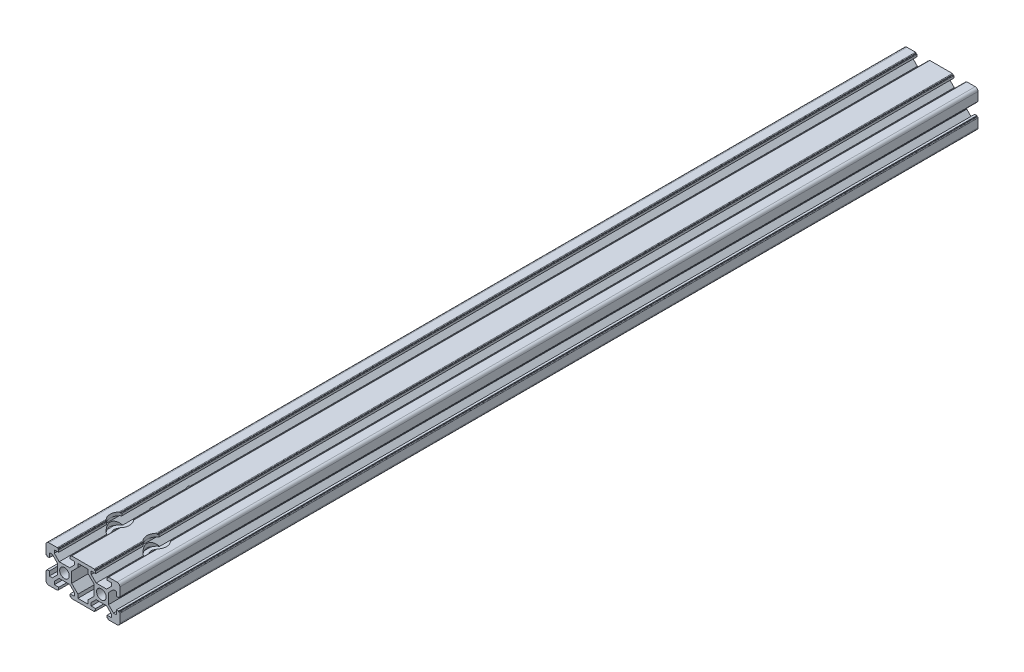
SolidWorks part; units mm, degrees
ref_plane "前视基准面" through (0, 0, 0) normal (0, 0, 1) x (1, 0, 0)
ref_plane "上视基准面" through (0, 0, 0) normal (0, 1, 0) x (1, 0, 0)
ref_plane "右视基准面" through (0, 0, 0) normal (1, 0, 0) x (0, 0, -1)
sketch "草图1" plane through (0, 0, 0) normal (0, 0, 1) x (1, 0, 0)
  line L0 (0, 0) -> (0, -41497.3383) construction
  line L1 (0, 0) -> (41497.3383, 0) construction
  line L2 (-13.9, 0) -> (-13.9, 2.8393)
  line L3 (-13.9, 2.8393) -> (-16.5607, 5.5)
  line L4 (-16.5607, 5.5) -> (-18.2, 5.5)
  line L5 (-18.2, 5.5) -> (-18.2, 3.1)
  line L6 (-18.2, 3.1) -> (-19.4, 3.1)
  line L7 (-19.4, 3.1) -> (-19.4, 3.6)
  line L8 (-19.4, 3.6) -> (-20, 3.6)
  line L9 (-20, 3.6) -> (-20, 10)
  line L10 (-20, 10) -> (-13.6, 10)
  line L11 (-13.6, 10) -> (-13.6, 9.4)
  line L12 (-13.6, 9.4) -> (-13.1, 9.4)
  line L13 (-13.1, 9.4) -> (-13.1, 8.2)
  line L14 (-13.1, 8.2) -> (-15.5, 8.2)
  line L15 (-15.5, 6.5607) -> (-12.8393, 3.9)
  line L16 (-12.8393, 3.9) -> (-7.1607, 3.9)
  line L17 (-4.5, 6.5607) -> (-7.1607, 3.9)
  line L18 (-4.5, 6.5607) -> (-4.5, 8.2)
  line L19 (-4.5, 8.2) -> (-6.9, 8.2)
  line L20 (-6.9, 8.2) -> (-6.9, 9.4)
  line L21 (-6.9, 9.4) -> (-6.4, 9.4)
  line L22 (-6.4, 9.4) -> (-6.4, 10)
  line L23 (-6.4, 10) -> (6.4, 10)
  line L24 (-15.5, 8.2) -> (-15.5, 6.5607)
  line L25 (-10, 0) -> (-20, 10) construction
  line L26 (-6.1, -2.8393) -> (-6.1, 2.8393)
  line L27 (-6.1, 2.8393) -> (-2.7, 6.2393)
  line L28 (-2.7, 6.2393) -> (-2.7, 8.2)
  line L29 (-2.7, 8.2) -> (2.7, 8.2)
  line L30 (-10, 0) -> (0, 10) construction
  line L31 (13.9, 0) -> (13.9, 2.8393)
  line L32 (6.1, -2.8393) -> (6.1, 2.8393)
  line L33 (4.5, 6.5607) -> (7.1607, 3.9)
  line L34 (12.8393, 3.9) -> (7.1607, 3.9)
  line L35 (6.1, 2.8393) -> (2.7, 6.2393)
  line L36 (2.7, 6.2393) -> (2.7, 8.2)
  line L37 (4.5, 6.5607) -> (4.5, 8.2)
  line L38 (6.4, 9.4) -> (6.4, 10)
  line L39 (6.9, 9.4) -> (6.4, 9.4)
  line L40 (6.9, 8.2) -> (6.9, 9.4)
  line L41 (4.5, 8.2) -> (6.9, 8.2)
  line L42 (13.1, 9.4) -> (13.1, 8.2)
  line L43 (13.6, 9.4) -> (13.1, 9.4)
  line L44 (13.6, 10) -> (13.6, 9.4)
  line L45 (20, 10) -> (13.6, 10)
  line L46 (20, 3.6) -> (20, 10)
  line L47 (19.4, 3.6) -> (20, 3.6)
  line L48 (19.4, 3.1) -> (19.4, 3.6)
  line L49 (18.2, 3.1) -> (19.4, 3.1)
  line L50 (18.2, 5.5) -> (18.2, 3.1)
  line L51 (16.5607, 5.5) -> (18.2, 5.5)
  line L52 (13.9, 2.8393) -> (16.5607, 5.5)
  line L53 (15.5, 6.5607) -> (12.8393, 3.9)
  line L54 (15.5, 8.2) -> (15.5, 6.5607)
  line L55 (13.1, 8.2) -> (15.5, 8.2)
  line L56 (15.5, -6.5607) -> (12.8393, -3.9)
  line L57 (13.9, -2.8393) -> (16.5607, -5.5)
  line L58 (16.5607, -5.5) -> (18.2, -5.5)
  line L59 (18.2, -5.5) -> (18.2, -3.1)
  line L60 (18.2, -3.1) -> (19.4, -3.1)
  line L61 (19.4, -3.1) -> (19.4, -3.6)
  line L62 (19.4, -3.6) -> (20, -3.6)
  line L63 (12.8393, -3.9) -> (7.1607, -3.9)
  line L64 (13.9, 0) -> (13.9, -2.8393)
  line L65 (13.1, -8.2) -> (15.5, -8.2)
  line L66 (15.5, -8.2) -> (15.5, -6.5607)
  line L67 (20, -3.6) -> (20, -10)
  line L68 (20, -10) -> (13.6, -10)
  line L69 (13.6, -10) -> (13.6, -9.4)
  line L70 (13.6, -9.4) -> (13.1, -9.4)
  line L71 (13.1, -9.4) -> (13.1, -8.2)
  line L72 (4.5, -8.2) -> (6.9, -8.2)
  line L73 (6.9, -8.2) -> (6.9, -9.4)
  line L74 (6.9, -9.4) -> (6.4, -9.4)
  line L75 (6.4, -9.4) -> (6.4, -10)
  line L76 (4.5, -6.5607) -> (4.5, -8.2)
  line L77 (2.7, -6.2393) -> (2.7, -8.2)
  line L78 (6.1, -2.8393) -> (2.7, -6.2393)
  line L79 (4.5, -6.5607) -> (7.1607, -3.9)
  line L80 (-2.7, -8.2) -> (2.7, -8.2)
  line L81 (-2.7, -6.2393) -> (-2.7, -8.2)
  line L82 (-6.1, -2.8393) -> (-2.7, -6.2393)
  line L83 (-4.5, -6.5607) -> (-7.1607, -3.9)
  line L84 (-4.5, -8.2) -> (-6.9, -8.2)
  line L85 (-4.5, -6.5607) -> (-4.5, -8.2)
  line L86 (-6.4, -10) -> (6.4, -10)
  line L87 (-6.4, -9.4) -> (-6.4, -10)
  line L88 (-6.9, -9.4) -> (-6.4, -9.4)
  line L89 (-6.9, -8.2) -> (-6.9, -9.4)
  line L90 (-13.1, -9.4) -> (-13.1, -8.2)
  line L91 (-13.6, -9.4) -> (-13.1, -9.4)
  line L92 (-13.6, -10) -> (-13.6, -9.4)
  line L93 (-15.5, -8.2) -> (-15.5, -6.5607)
  line L94 (-13.1, -8.2) -> (-15.5, -8.2)
  line L95 (-12.8393, -3.9) -> (-7.1607, -3.9)
  line L96 (-15.5, -6.5607) -> (-12.8393, -3.9)
  line L97 (-13.9, 0) -> (-13.9, -2.8393)
  line L98 (-13.9, -2.8393) -> (-16.5607, -5.5)
  line L99 (-19.4, -3.6) -> (-20, -3.6)
  line L100 (-19.4, -3.1) -> (-19.4, -3.6)
  line L101 (-18.2, -3.1) -> (-19.4, -3.1)
  line L102 (-18.2, -5.5) -> (-18.2, -3.1)
  line L103 (-16.5607, -5.5) -> (-18.2, -5.5)
  line L104 (-20, -3.6) -> (-20, -10)
  line L105 (-20, -10) -> (-13.6, -10)
  circle A0 centre (-10, 0) radius 2.6
  circle A1 centre (10, 0) radius 2.6
  point P50 (0, 8.2)
  point P95 (6.1, 0)
  point P96 (-6.1, 0)
  dimension "D1" = 5.2
  dimension "D2" = 45
  dimension "D3" = 1.5
  dimension "D4" = 20
  dimension "D5" = 40
  dimension "D6" = 0.75
  dimension "D7" = 7.2
  dimension "D8" = 6.2
  dimension "D9" = 6.1
  dimension "D10" = 1.8
  dimension "D11" = 1.2
  dimension "D12" = 12.2
  dimension "D13" = 5.4
  dimension "D14" = 11
  dimension "D15" = 1.5
  dimension "D16" = 0.75
extrude "凸台-拉伸1" add sketch "草图1" along normal mid plane 465
fillet "圆角1" radius 1.5 4 edges at (20, -10, 0) (20, 10, 0) (-20, -10, 0) (-20, 10, 0)
fillet "圆角2" radius 0.3 12 edges at (-6.4, 10, 0) (-13.6, 10, 0) (-20, 3.6, 0) (-20, -3.6, 0) (-13.6, -10, 0) (-6.4, -10, 0) (6.4, -10, 0) (20, -3.6, 0) (20, 3.6, 0) (13.6, -10, 0) (13.6, 10, 0) (6.4, 10, 0)
sketch "草图2" plane through (0, -3.9, 0) normal (0, -1, 0) x (1, 0, 0)
  line L0 (10, 202.5) -> (-10, 202.5) construction
  circle A0 centre (-10, 202.5) radius 3.1
  circle A1 centre (10, 202.5) radius 3.1
  point P3 (0, 202.5)
  dimension "D2" = 30
  dimension "D3" = 6.2
  dimension "D1" = 20
extrude "切除-拉伸1" cut sketch "草图2" against normal through all both and the other way through all
sketch "草图3" plane through (0, 3.9, 0) normal (0, 1, 0) x (1, 0, 0)
  circle A0 centre (-10, -202.5) radius 5.25
  circle A1 centre (10, -202.5) radius 5.25
  dimension "D1" = 10.5
extrude "切除-拉伸2" cut sketch "草图3" along normal through all
sketch "草图4" plane through (0, 3.9, 0) normal (0, 1, 0) x (1, 0, 0)
  line L0 (-10, -162.5) -> (-10, -182.5) construction
  line L2 (-20, -232.5) -> (-20, 232.5) construction
  circle A0 centre (-10, -182.5) radius 3.1
  circle A1 centre (-10, -162.5) radius 3.1
  circle A2 centre (10, -202.5) radius 3.1 construction
  dimension "D1" = 20
  dimension "D2" = 20
  dimension "D3" = 6.2
  dimension "D4" = 10
extrude "切除-拉伸3" cut sketch "草图4" against normal through all both and the other way through all
sketch "草图6" plane through (0, -3.9, 0) normal (0, -1, 0) x (1, 0, 0)
  circle A0 centre (-10, 182.5) radius 5.25
  circle A1 centre (-10, 162.5) radius 5.25
  dimension "D1" = 10.5
extrude "切除-拉伸4" cut sketch "草图6" along normal through all
equation "\"D6@草图1\"=1/2*\"D3@草图1\""
equation "\"D16@草图1\"=0.5*\"D15@草图1\""
